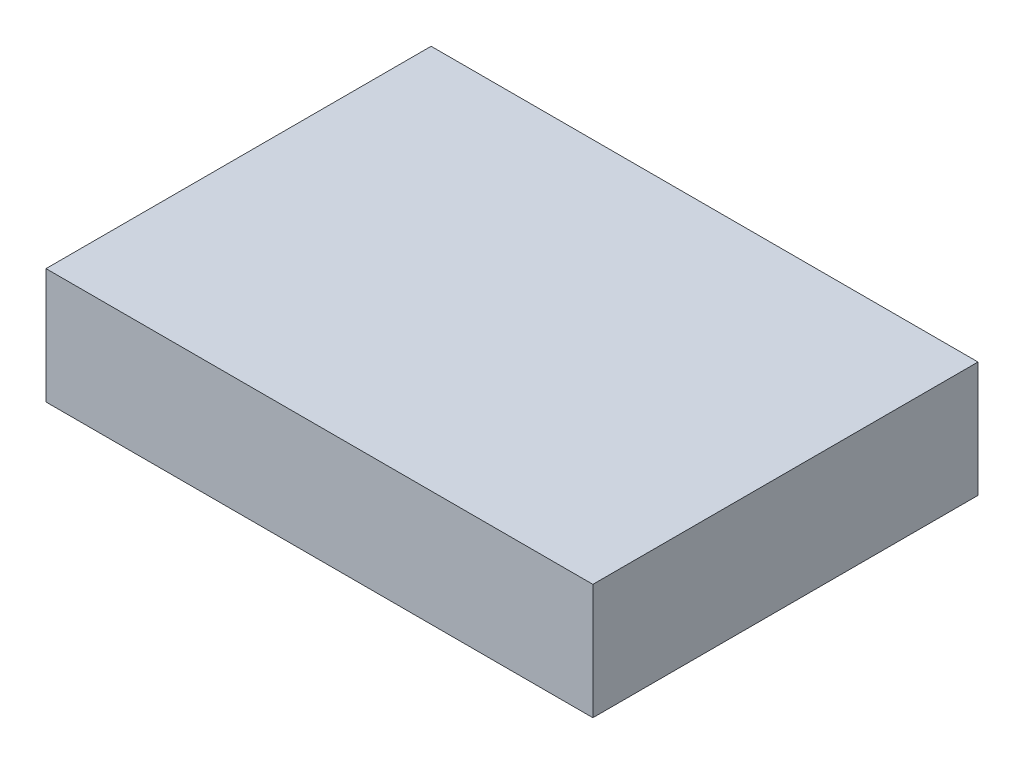
SolidWorks part; units mm, degrees
ref_plane "前视基准面" through (0, 0, 0) normal (0, 0, 1) x (1, 0, 0)
ref_plane "上视基准面" through (0, 0, 0) normal (0, 1, 0) x (1, 0, 0)
ref_plane "右视基准面" through (0, 0, 0) normal (1, 0, 0) x (0, 0, -1)
other "Configuration Table"
sketch "草图1" plane through (0, 0, 0) normal (0, 1, 0) x (1, 0, 0)
  line L1 (0, 0) -> (71, 0)
  line L2 (0, 0) -> (0, -50)
  line L3 (0, -50) -> (71, -50)
  line L4 (71, 0) -> (71, -50)
  dimension "D1" = 50
  dimension "D2" = 71
extrude "凸台-拉伸1" add sketch "草图1" along normal blind 15
